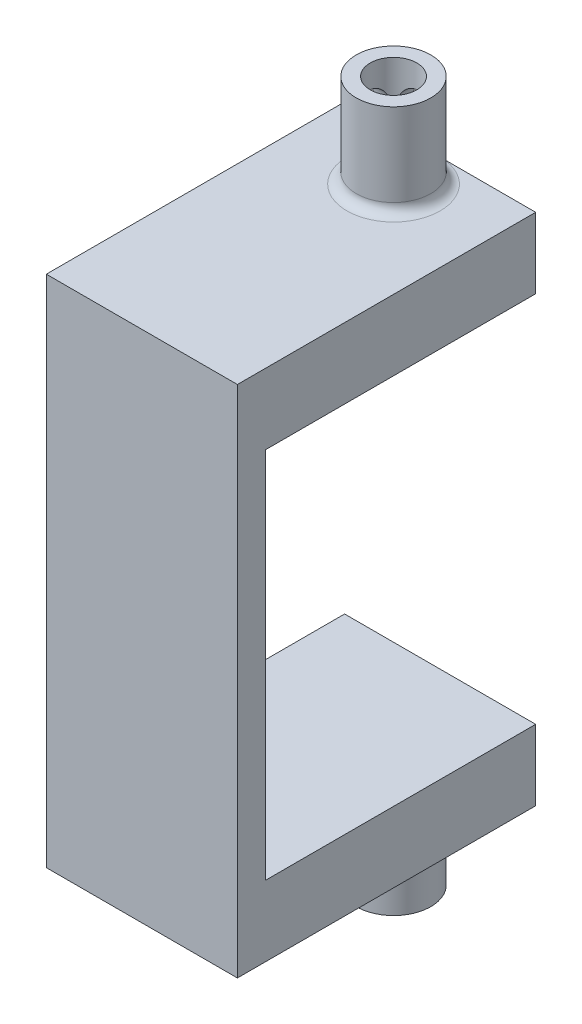
SolidWorks part; units mm, degrees
ref_plane "前视基准面" through (0, 0, 0) normal (0, 0, 1) x (1, 0, 0)
ref_plane "上视基准面" through (0, 0, 0) normal (0, 1, 0) x (1, 0, 0)
ref_plane "右视基准面" through (0, 0, 0) normal (1, 0, 0) x (0, 0, -1)
other "Configuration Table"
sketch "草图1" plane through (0, 0, 0) normal (0, 0, 1) x (1, 0, 0)
  line L0 (-1000, 0) -> (49000, 0) construction
  line L1 (-10.25, -20) -> (10.25, -20)
  line L2 (-10.25, -20) -> (-10.25, 20)
  line L3 (-10.25, 20) -> (10.25, 20)
  line L4 (10.25, -20) -> (10.25, 20)
  line L5 (-10.25, -20) -> (10.25, 20) construction
  line L6 (-10.25, 20) -> (10.25, -20) construction
  line L7 (-5, 15) -> (5, 15)
  line L8 (-5, 15) -> (-5, 25)
  line L9 (-5, 25) -> (5, 25)
  line L10 (5, 15) -> (5, 25)
  line L11 (-5, 15) -> (5, 25) construction
  line L12 (-5, 25) -> (5, 15) construction
  line L14 (-10.25, -35.1417) -> (10.25, -35.1417)
  line L15 (-10.25, -35.1417) -> (-10.25, 35.1417)
  line L16 (-10.25, 35.1417) -> (10.25, 35.1417)
  line L17 (10.25, -35.1417) -> (10.25, 35.1417)
  line L18 (-10.25, -35.1417) -> (10.25, 35.1417) construction
  line L19 (-10.25, 35.1417) -> (10.25, -35.1417) construction
  circle A0 centre (-5, 25) radius 2
  circle A1 centre (5, 25) radius 2
  circle A2 centre (5, -25) radius 2
  circle A3 centre (-5, -25) radius 2
  point P0 (0, 0)
  point P6 (0, 20)
  point P19 (0, 0)
  dimension "D5" = 4
  dimension "D6" = 4
  dimension "D1" = 20.5
  dimension "D2" = 40
  dimension "D3" = 10
  dimension "D4" = 10
extrude "凸台-拉伸1" add sketch "草图1" along normal blind 29 contours A1 L10 L3 L17 L16 L15 L8 A0 L9 | L14 L17 L1 L15 A2 A3 | A1 L9 A0 L8 L3 L10
sketch "草图2" plane through (0, 0, 29) normal (0, 0, 1) x (1, 0, 0)
  line L1 (-10.25, 35.1417) -> (10.25, 35.1417)
  line L2 (-10.25, 35.1417) -> (-10.25, -35.1417)
  line L3 (-10.25, -35.1417) -> (10.25, -35.1417)
  line L4 (10.25, 35.1417) -> (10.25, -35.1417)
extrude "凸台-拉伸2" add sketch "草图2" along normal blind 3
sketch "草图3" plane through (0, 0, 0) normal (0, 0, -1) x (-1, 0, 0)
  line L0 (-10.25, -35.1417) -> (-10.25, -20) construction
  line L1 (-10.25, -27.5709) -> (10.25, -27.5709)
  line L2 (-10.25, -27.5709) -> (-10.25, 27.5709)
  line L3 (-10.25, 27.5709) -> (10.25, 27.5709)
  line L4 (10.25, -27.5709) -> (10.25, 27.5709)
  line L5 (10.25, 20) -> (10.25, 35.1417) construction
  line L7 (-10.25, -35.1417) -> (10.25, -35.1417)
  line L8 (-10.25, -35.1417) -> (-10.25, 35.1417)
  line L9 (-10.25, 35.1417) -> (10.25, 35.1417)
  line L10 (10.25, -35.1417) -> (10.25, 35.1417)
  line M2 (-10.25, -35.1417) -> (10.25, -35.1417)
  line M3 (10.25, -35.1417) -> (10.25, -20)
  line M5 (-10.25, -20) -> (-10.25, -35.1417)
extrude "切除-拉伸1" cut sketch "草图3" against normal through all contours L1 M5 M2 M3 | L3 L10 L9 L8
sketch "草图5" plane through (0, -27.5709, 0) normal (0, -1, 0) x (1, 0, 0)
  line L0 (0, 0) -> (0, 2.5)
  circle A0 centre (0, 2.5) radius 2.5
  dimension "D2" = 5
  dimension "D1" = 2.5
extrude "凸台-拉伸3" add sketch "草图5" along normal blind 10
sketch "草图8" plane through (0, 27.5709, 0) normal (0, 1, 0) x (1, 0, 0)
  line L0 (0, 0) -> (0, -2.5)
  line L1 (0, -2.5) -> (0, -16.5)
  line L2 (0, -16.5) -> (0, -26.5)
  circle A0 centre (0, -16.5) radius 1.6
  circle A1 centre (0, -26.5) radius 1.6
  dimension "D4" = 3.2
  dimension "D5" = 3.2
  dimension "D1" = 2.5
  dimension "D2" = 14
  dimension "D3" = 10
extrude "切除-拉伸2" cut sketch "草图8" against normal up to next
sketch "草图9" plane through (0, -27.5709, 0) normal (0, -1, 0) x (1, 0, 0)
  line L1 (-10.25, 32) -> (10.25, 32)
  line L2 (-10.25, 32) -> (-10.25, 0)
  line L3 (-10.25, 0) -> (10.25, 0)
  line L4 (10.25, 32) -> (10.25, 0)
extrude "切除-拉伸3" cut sketch "草图9" along normal through all
sketch "草图12" plane through (0, 0, 0) normal (0, 0, -1) x (-1, 0, 0)
  line L1 (-10.25, 27.5709) -> (10.25, 27.5709)
  line L2 (-10.25, 27.5709) -> (-10.25, 20)
  line L3 (-10.25, 20) -> (10.25, 20)
  line L4 (10.25, 27.5709) -> (10.25, 20)
  circle A0 centre (-5, 25) radius 2
  circle A1 centre (5, 25) radius 2
extrude "凸台-拉伸5" add sketch "草图12" against normal blind 30
sketch "草图13" plane through (0, 27.5709, 0) normal (0, 1, 0) x (1, 0, 0)
  line L0 (0, 0) -> (0, -32)
  line L1 (10.25, -32) -> (-10.25, -32) construction
  line L2 (0, 0) -> (0, -10)
  line L3 (0, 0) -> (0, -2.5275)
  line L4 (0, 0) -> (0, -5)
  circle A2 centre (0, -5) radius 2.5
  circle A3 centre (0, -5) radius 4
  dimension "D3" = 5
  dimension "D4" = 5
  dimension "D5" = 8
  dimension "D1" = 32
  dimension "D2" = 10
extrude "凸台-拉伸6" add sketch "草图13" along normal blind 10 contours L4 A3 L2 A2 | L2 A3 L4 A2
sketch "草图15" plane through (0, 0, 0) normal (1, 0, 0) x (0, 0, -1)
  line L0 (-1, 27.5709) -> (0, 27.5709)
  line L1 (-1, 27.5709) -> (-1, 28.676)
  line L2 (-1, 27.5709) -> (-1, 37.5709) construction
  line L3 (-5, -962.4291) -> (-5, 49037.5709) construction
  line L4 (-2.5, 37.5709) -> (-7.5, 37.5709) construction
  arc A0 (-1, 28.676) -> (0, 27.5709) centre (0.1107, 28.676) ccw
  point P13 (-5, 37.5709)
revolve "旋转1" add sketch "草图15" angle 360 about L3
ref_plane "基准面1" through (0, 0, 5) normal (0, 0, 1) x (1, 0, 0)
sketch "草图16" plane through (0, 0, 5) normal (0, 0, 1) x (1, 0, 0)
  line L0 (0, 37.5709) -> (0, 33.5709)
  line L1 (2.5, 37.5709) -> (-2.5, 37.5709) construction
  circle A0 centre (0, 33.5709) radius 1.5
  dimension "D2" = 3
  dimension "D1" = 4
extrude "切除-拉伸5" cut sketch "草图16" against normal through all
sketch "草图17" plane through (0, 0, 0) normal (1, 0, 0) x (0, 0, -1)
  line L0 (-5, 37.5709) -> (-5, 33.5709)
  line L1 (-2.5, 37.5709) -> (-7.5, 37.5709) construction
  line L2 (-5, 11.275) -> (-5, -11.275) construction
  circle A0 centre (-5, 33.5709) radius 1.5
  dimension "D2" = 3
  dimension "D1" = 4
extrude "切除-拉伸6" cut sketch "草图17" against normal through all
sketch "草图19" plane through (0, -27.5709, 0) normal (0, -1, 0) x (1, 0, 0)
  line L0 (0, 0) -> (0, 5)
  line L1 (10.25, 0) -> (-10.25, 0) construction
  circle A0 centre (0, 5) radius 2.5
  circle A1 centre (0, 5) radius 4
  dimension "D2" = 5
  dimension "D3" = 8
  dimension "D1" = 5
extrude "凸台-拉伸7" add sketch "草图19" along normal blind 10
sketch "草图20" plane through (0, 0, 0) normal (1, 0, 0) x (0, 0, -1)
  line L0 (-1, -27.5709) -> (0, -27.5709)
  line L1 (-1, -27.5709) -> (-1, -28.5709)
  line L2 (-1, -37.5709) -> (-1, -27.5709) construction
  line L3 (-5, -1027.5709) -> (-5, 48972.4291) construction
  line L4 (-9, -27.5709) -> (-1, -27.5709) construction
  arc A0 (-1, -28.5709) -> (0, -27.5709) centre (0, -28.5709) cw
  point P13 (-5, -27.5709)
  dimension "D1" = 1
revolve "旋转2" add sketch "草图20" angle 360 about L3
sketch "草图21" plane through (0, 0, 5) normal (0, 0, 1) x (1, 0, 0)
  line L0 (0, -37.5709) -> (0, -33.5709)
  line L1 (-4, -37.5709) -> (4, -37.5709) construction
  circle A0 centre (0, -33.5709) radius 1.5
  dimension "D2" = 3
  dimension "D1" = 4
extrude "切除-拉伸7" cut sketch "草图21" against normal through all
sketch "草图22" plane through (0, 0, 0) normal (1, 0, 0) x (0, 0, -1)
  line L0 (-5, -37.5709) -> (-5, -33.5709)
  line L1 (-9, -37.5709) -> (-1, -37.5709) construction
  line L2 (-5, 11.275) -> (-5, -11.275) construction
  circle A0 centre (-5, -33.5709) radius 1.5
  dimension "D2" = 3
  dimension "D1" = 4
extrude "切除-拉伸8" cut sketch "草图22" against normal through all
